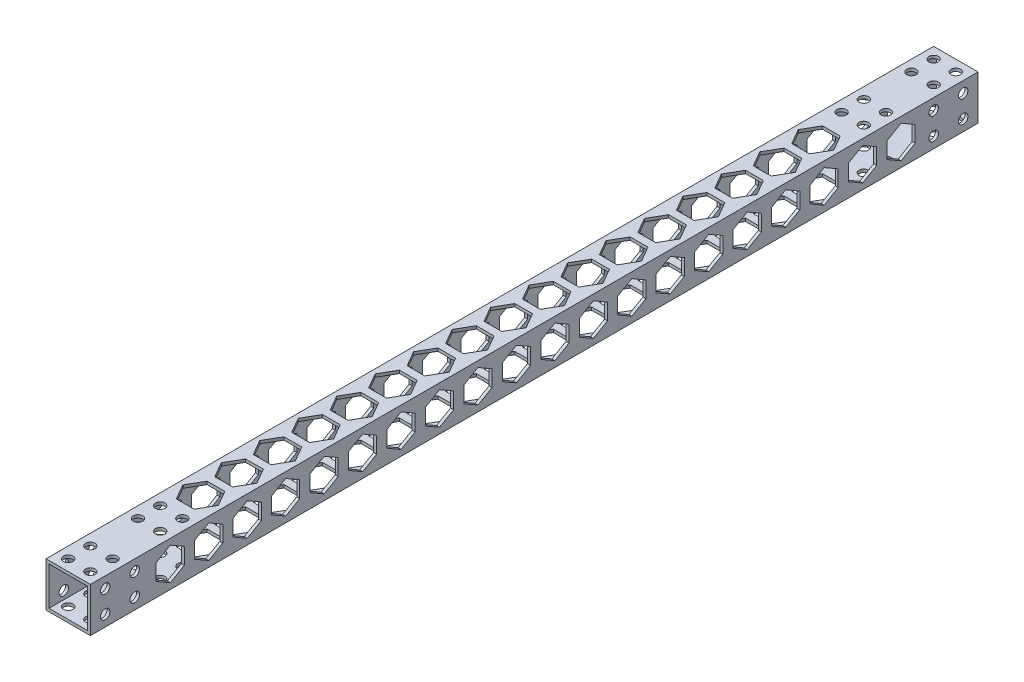
SolidWorks part; units mm, degrees
ref_plane "前视基准面" through (0, 0, 0) normal (0, 0, 1) x (1, 0, 0)
ref_plane "上视基准面" through (0, 0, 0) normal (0, 1, 0) x (1, 0, 0)
ref_plane "右视基准面" through (0, 0, 0) normal (1, 0, 0) x (0, 0, -1)
other "Configuration Table"
sketch "草图1" plane through (0, 0, 0) normal (0, 0, 1) x (1, 0, 0)
  line L1 (0, 0) -> (15, 0)
  line L2 (0, 0) -> (0, -15)
  line L3 (0, -15) -> (15, -15)
  line L4 (15, 0) -> (15, -15)
  dimension "D1" = 15
  dimension "D2" = 15
extrude "拉伸-薄壁1" add sketch "草图1" along normal blind 300 thin
sketch "草图2" plane through (15, 0, 0) normal (1, 0, 0) x (0, 0, -1)
  line L0 (-260, -2) -> (-264.7631, -4.75)
  line L1 (-300, 0) -> (0, 0) construction
  line L2 (-300, -15) -> (0, -15) construction
  line L3 (-290, 0) -> (-290, -15) construction
  line L4 (-300, -15) -> (-300, 0) construction
  line L5 (-300, -7.5) -> (-290, -7.5) construction
  line L6 (-10, 0) -> (-10, -15) construction
  line L7 (0, -7.5) -> (-10, -7.5) construction
  line L8 (0, -15) -> (0, 0) construction
  line L9 (-273, -7.5) -> (-290, -7.5) construction
  line L10 (-273, -2) -> (-277.7631, -4.75)
  line L11 (-277.7631, -4.75) -> (-277.7631, -10.25)
  line L12 (-277.7631, -10.25) -> (-273, -13)
  line L13 (-273, -13) -> (-268.2369, -10.25)
  line L14 (-268.2369, -10.25) -> (-268.2369, -4.75)
  line L15 (-268.2369, -4.75) -> (-273, -2)
  line L16 (-255.2369, -4.75) -> (-260, -2)
  line L17 (-255.2369, -10.25) -> (-255.2369, -4.75)
  line L18 (-260, -13) -> (-255.2369, -10.25)
  line L19 (-264.7631, -10.25) -> (-260, -13)
  line L20 (-264.7631, -4.75) -> (-264.7631, -10.25)
  line L21 (-247, -2) -> (-251.7631, -4.75)
  line L22 (-242.2369, -4.75) -> (-247, -2)
  line L23 (-242.2369, -10.25) -> (-242.2369, -4.75)
  line L24 (-247, -13) -> (-242.2369, -10.25)
  line L25 (-251.7631, -10.25) -> (-247, -13)
  line L26 (-251.7631, -4.75) -> (-251.7631, -10.25)
  line L27 (-234, -2) -> (-238.7631, -4.75)
  line L28 (-229.2369, -4.75) -> (-234, -2)
  line L29 (-229.2369, -10.25) -> (-229.2369, -4.75)
  line L30 (-234, -13) -> (-229.2369, -10.25)
  line L31 (-238.7631, -10.25) -> (-234, -13)
  line L32 (-238.7631, -4.75) -> (-238.7631, -10.25)
  line L33 (-221, -2) -> (-225.7631, -4.75)
  line L34 (-216.2369, -4.75) -> (-221, -2)
  line L35 (-216.2369, -10.25) -> (-216.2369, -4.75)
  line L36 (-221, -13) -> (-216.2369, -10.25)
  line L37 (-225.7631, -10.25) -> (-221, -13)
  line L38 (-225.7631, -4.75) -> (-225.7631, -10.25)
  line L39 (-208, -2) -> (-212.7631, -4.75)
  line L40 (-203.2369, -4.75) -> (-208, -2)
  line L41 (-203.2369, -10.25) -> (-203.2369, -4.75)
  line L42 (-208, -13) -> (-203.2369, -10.25)
  line L43 (-212.7631, -10.25) -> (-208, -13)
  line L44 (-212.7631, -4.75) -> (-212.7631, -10.25)
  line L45 (-195, -2) -> (-199.7631, -4.75)
  line L46 (-190.2369, -4.75) -> (-195, -2)
  line L47 (-190.2369, -10.25) -> (-190.2369, -4.75)
  line L48 (-195, -13) -> (-190.2369, -10.25)
  line L49 (-199.7631, -10.25) -> (-195, -13)
  line L50 (-199.7631, -4.75) -> (-199.7631, -10.25)
  line L51 (-182, -2) -> (-186.7631, -4.75)
  line L52 (-177.2369, -4.75) -> (-182, -2)
  line L53 (-177.2369, -10.25) -> (-177.2369, -4.75)
  line L54 (-182, -13) -> (-177.2369, -10.25)
  line L55 (-186.7631, -10.25) -> (-182, -13)
  line L56 (-186.7631, -4.75) -> (-186.7631, -10.25)
  line L57 (-169, -2) -> (-173.7631, -4.75)
  line L58 (-164.2369, -4.75) -> (-169, -2)
  line L59 (-164.2369, -10.25) -> (-164.2369, -4.75)
  line L60 (-169, -13) -> (-164.2369, -10.25)
  line L61 (-173.7631, -10.25) -> (-169, -13)
  line L62 (-173.7631, -4.75) -> (-173.7631, -10.25)
  line L63 (-156, -2) -> (-160.7631, -4.75)
  line L64 (-151.2369, -4.75) -> (-156, -2)
  line L65 (-151.2369, -10.25) -> (-151.2369, -4.75)
  line L66 (-156, -13) -> (-151.2369, -10.25)
  line L67 (-160.7631, -10.25) -> (-156, -13)
  line L68 (-160.7631, -4.75) -> (-160.7631, -10.25)
  line L69 (-143, -2) -> (-147.7631, -4.75)
  line L70 (-138.2369, -4.75) -> (-143, -2)
  line L71 (-138.2369, -10.25) -> (-138.2369, -4.75)
  line L72 (-143, -13) -> (-138.2369, -10.25)
  line L73 (-147.7631, -10.25) -> (-143, -13)
  line L74 (-147.7631, -4.75) -> (-147.7631, -10.25)
  line L75 (-130, -2) -> (-134.7631, -4.75)
  line L76 (-125.2369, -4.75) -> (-130, -2)
  line L77 (-125.2369, -10.25) -> (-125.2369, -4.75)
  line L78 (-130, -13) -> (-125.2369, -10.25)
  line L79 (-134.7631, -10.25) -> (-130, -13)
  line L80 (-134.7631, -4.75) -> (-134.7631, -10.25)
  line L81 (-117, -2) -> (-121.7631, -4.75)
  line L82 (-112.2369, -4.75) -> (-117, -2)
  line L83 (-112.2369, -10.25) -> (-112.2369, -4.75)
  line L84 (-117, -13) -> (-112.2369, -10.25)
  line L85 (-121.7631, -10.25) -> (-117, -13)
  line L86 (-121.7631, -4.75) -> (-121.7631, -10.25)
  line L87 (-104, -2) -> (-108.7631, -4.75)
  line L88 (-99.2369, -4.75) -> (-104, -2)
  line L89 (-99.2369, -10.25) -> (-99.2369, -4.75)
  line L90 (-104, -13) -> (-99.2369, -10.25)
  line L91 (-108.7631, -10.25) -> (-104, -13)
  line L92 (-108.7631, -4.75) -> (-108.7631, -10.25)
  line L93 (-91, -2) -> (-95.7631, -4.75)
  line L94 (-86.2369, -4.75) -> (-91, -2)
  line L95 (-86.2369, -10.25) -> (-86.2369, -4.75)
  line L96 (-91, -13) -> (-86.2369, -10.25)
  line L97 (-95.7631, -10.25) -> (-91, -13)
  line L98 (-95.7631, -4.75) -> (-95.7631, -10.25)
  line L99 (-78, -2) -> (-82.7631, -4.75)
  line L100 (-73.2369, -4.75) -> (-78, -2)
  line L101 (-73.2369, -10.25) -> (-73.2369, -4.75)
  line L102 (-78, -13) -> (-73.2369, -10.25)
  line L103 (-82.7631, -10.25) -> (-78, -13)
  line L104 (-82.7631, -4.75) -> (-82.7631, -10.25)
  line L105 (-65, -2) -> (-69.7631, -4.75)
  line L106 (-60.2369, -4.75) -> (-65, -2)
  line L107 (-60.2369, -10.25) -> (-60.2369, -4.75)
  line L108 (-65, -13) -> (-60.2369, -10.25)
  line L109 (-69.7631, -10.25) -> (-65, -13)
  line L110 (-69.7631, -4.75) -> (-69.7631, -10.25)
  line L111 (-52, -2) -> (-56.7631, -4.75)
  line L112 (-47.2369, -4.75) -> (-52, -2)
  line L113 (-47.2369, -10.25) -> (-47.2369, -4.75)
  line L114 (-52, -13) -> (-47.2369, -10.25)
  line L115 (-56.7631, -10.25) -> (-52, -13)
  line L116 (-56.7631, -4.75) -> (-56.7631, -10.25)
  line L117 (-39, -2) -> (-43.7631, -4.75)
  line L118 (-34.2369, -4.75) -> (-39, -2)
  line L119 (-34.2369, -10.25) -> (-34.2369, -4.75)
  line L120 (-39, -13) -> (-34.2369, -10.25)
  line L121 (-43.7631, -10.25) -> (-39, -13)
  line L122 (-43.7631, -4.75) -> (-43.7631, -10.25)
  line L123 (-26, -2) -> (-30.7631, -4.75)
  line L124 (-21.2369, -4.75) -> (-26, -2)
  line L125 (-21.2369, -10.25) -> (-21.2369, -4.75)
  line L126 (-26, -13) -> (-21.2369, -10.25)
  line L127 (-30.7631, -10.25) -> (-26, -13)
  line L128 (-30.7631, -4.75) -> (-30.7631, -10.25)
  circle A0 centre (-295, -3.75) radius 1.6
  circle A1 centre (-295, -11.25) radius 1.6
  circle A2 centre (-285, -11.25) radius 1.6
  circle A3 centre (-285, -3.75) radius 1.6
  circle A8 centre (-5, -3.75) radius 1.6
  circle A9 centre (-5, -11.25) radius 1.6
  circle A10 centre (-15, -11.25) radius 1.6
  circle A11 centre (-15, -3.75) radius 1.6
  circle A12 centre (-273, -7.5) radius 4.7631 construction
  dimension "D2" = 3.2
  dimension "D6" = 3.2
  dimension "D1" = 10
  dimension "D3" = 5
  dimension "D4" = 3.75
  dimension "D5" = 10
  dimension "D7" = 3.75
  dimension "D8" = 5
  dimension "D9" = 5.5
  dimension "D10" = 17
  dimension "D12" = 13
  dimension "D11" = 20
extrude "切除-拉伸1" cut sketch "草图2" against normal through all
sketch "草图3" plane through (0, 0, 0) normal (0, 1, 0) x (1, 0, 0)
  line L0 (7.5, 0) -> (7.5, -300) construction
  line L1 (15, 0) -> (0, 0) construction
  line L2 (15, -300) -> (0, -300) construction
  line L3 (15, -150) -> (0, -150) construction
  line L4 (15, -300) -> (15, 0) construction
  line L5 (0, -300) -> (0, 0) construction
  line L6 (0, -7.5) -> (15, -7.5) construction
  line L7 (0, -292.5) -> (15, -292.5) construction
  line L8 (10.5, -55.0538) -> (4.5, -55.0538)
  line L9 (4.5, -42.0538) -> (1.5, -47.25)
  line L10 (1.5, -47.25) -> (4.5, -52.4462)
  line L11 (4.5, -52.4462) -> (10.5, -52.4462)
  line L12 (10.5, -52.4462) -> (13.5, -47.25)
  line L13 (13.5, -47.25) -> (10.5, -42.0538)
  line L14 (10.5, -42.0538) -> (4.5, -42.0538)
  line L15 (13.5, -60.25) -> (10.5, -55.0538)
  line L16 (10.5, -65.4462) -> (13.5, -60.25)
  line L17 (4.5, -65.4462) -> (10.5, -65.4462)
  line L18 (1.5, -60.25) -> (4.5, -65.4462)
  line L19 (4.5, -55.0538) -> (1.5, -60.25)
  line L20 (10.5, -68.0538) -> (4.5, -68.0538)
  line L21 (13.5, -73.25) -> (10.5, -68.0538)
  line L22 (10.5, -78.4462) -> (13.5, -73.25)
  line L23 (4.5, -78.4462) -> (10.5, -78.4462)
  line L24 (1.5, -73.25) -> (4.5, -78.4462)
  line L25 (4.5, -68.0538) -> (1.5, -73.25)
  line L26 (10.5, -81.0538) -> (4.5, -81.0538)
  line L27 (13.5, -86.25) -> (10.5, -81.0538)
  line L28 (10.5, -91.4462) -> (13.5, -86.25)
  line L29 (4.5, -91.4462) -> (10.5, -91.4462)
  line L30 (1.5, -86.25) -> (4.5, -91.4462)
  line L31 (4.5, -81.0538) -> (1.5, -86.25)
  line L32 (10.5, -94.0538) -> (4.5, -94.0538)
  line L33 (13.5, -99.25) -> (10.5, -94.0538)
  line L34 (10.5, -104.4462) -> (13.5, -99.25)
  line L35 (4.5, -104.4462) -> (10.5, -104.4462)
  line L36 (1.5, -99.25) -> (4.5, -104.4462)
  line L37 (4.5, -94.0538) -> (1.5, -99.25)
  line L38 (10.5, -107.0538) -> (4.5, -107.0538)
  line L39 (13.5, -112.25) -> (10.5, -107.0538)
  line L40 (10.5, -117.4462) -> (13.5, -112.25)
  line L41 (4.5, -117.4462) -> (10.5, -117.4462)
  line L42 (1.5, -112.25) -> (4.5, -117.4462)
  line L43 (4.5, -107.0538) -> (1.5, -112.25)
  line L44 (10.5, -120.0538) -> (4.5, -120.0538)
  line L45 (13.5, -125.25) -> (10.5, -120.0538)
  line L46 (10.5, -130.4462) -> (13.5, -125.25)
  line L47 (4.5, -130.4462) -> (10.5, -130.4462)
  line L48 (1.5, -125.25) -> (4.5, -130.4462)
  line L49 (4.5, -120.0538) -> (1.5, -125.25)
  line L50 (10.5, -133.0538) -> (4.5, -133.0538)
  line L51 (13.5, -138.25) -> (10.5, -133.0538)
  line L52 (10.5, -143.4462) -> (13.5, -138.25)
  line L53 (4.5, -143.4462) -> (10.5, -143.4462)
  line L54 (1.5, -138.25) -> (4.5, -143.4462)
  line L55 (4.5, -133.0538) -> (1.5, -138.25)
  line L56 (10.5, -146.0538) -> (4.5, -146.0538)
  line L57 (13.5, -151.25) -> (10.5, -146.0538)
  line L58 (10.5, -156.4462) -> (13.5, -151.25)
  line L59 (4.5, -156.4462) -> (10.5, -156.4462)
  line L60 (1.5, -151.25) -> (4.5, -156.4462)
  line L61 (4.5, -146.0538) -> (1.5, -151.25)
  line L62 (10.5, -159.0538) -> (4.5, -159.0538)
  line L63 (13.5, -164.25) -> (10.5, -159.0538)
  line L64 (10.5, -169.4462) -> (13.5, -164.25)
  line L65 (4.5, -169.4462) -> (10.5, -169.4462)
  line L66 (1.5, -164.25) -> (4.5, -169.4462)
  line L67 (4.5, -159.0538) -> (1.5, -164.25)
  line L68 (10.5, -172.0538) -> (4.5, -172.0538)
  line L69 (13.5, -177.25) -> (10.5, -172.0538)
  line L70 (10.5, -182.4462) -> (13.5, -177.25)
  line L71 (4.5, -182.4462) -> (10.5, -182.4462)
  line L72 (1.5, -177.25) -> (4.5, -182.4462)
  line L73 (4.5, -172.0538) -> (1.5, -177.25)
  line L74 (10.5, -185.0538) -> (4.5, -185.0538)
  line L75 (13.5, -190.25) -> (10.5, -185.0538)
  line L76 (10.5, -195.4462) -> (13.5, -190.25)
  line L77 (4.5, -195.4462) -> (10.5, -195.4462)
  line L78 (1.5, -190.25) -> (4.5, -195.4462)
  line L79 (4.5, -185.0538) -> (1.5, -190.25)
  line L80 (10.5, -198.0538) -> (4.5, -198.0538)
  line L81 (13.5, -203.25) -> (10.5, -198.0538)
  line L82 (10.5, -208.4462) -> (13.5, -203.25)
  line L83 (4.5, -208.4462) -> (10.5, -208.4462)
  line L84 (1.5, -203.25) -> (4.5, -208.4462)
  line L85 (4.5, -198.0538) -> (1.5, -203.25)
  line L86 (10.5, -211.0538) -> (4.5, -211.0538)
  line L87 (13.5, -216.25) -> (10.5, -211.0538)
  line L88 (10.5, -221.4462) -> (13.5, -216.25)
  line L89 (4.5, -221.4462) -> (10.5, -221.4462)
  line L90 (1.5, -216.25) -> (4.5, -221.4462)
  line L91 (4.5, -211.0538) -> (1.5, -216.25)
  line L134 (0, -31.1) -> (15, -31.1) construction
  line L135 (10.5, -224.0538) -> (4.5, -224.0538)
  line L136 (13.5, -229.25) -> (10.5, -224.0538)
  line L137 (10.5, -234.4462) -> (13.5, -229.25)
  line L138 (4.5, -234.4462) -> (10.5, -234.4462)
  line L139 (1.5, -229.25) -> (4.5, -234.4462)
  line L140 (4.5, -224.0538) -> (1.5, -229.25)
  line L159 (0, -268.9) -> (15, -268.9) construction
  line L160 (10.5, -237.0538) -> (4.5, -237.0538)
  line L161 (13.5, -242.25) -> (10.5, -237.0538)
  line L162 (10.5, -247.4462) -> (13.5, -242.25)
  line L163 (4.5, -247.4462) -> (10.5, -247.4462)
  line L164 (1.5, -242.25) -> (4.5, -247.4462)
  line L165 (4.5, -237.0538) -> (1.5, -242.25)
  line L166 (10.5, -250.0538) -> (4.5, -250.0538)
  line L167 (13.5, -255.25) -> (10.5, -250.0538)
  line L168 (10.5, -260.4462) -> (13.5, -255.25)
  line L169 (4.5, -260.4462) -> (10.5, -260.4462)
  line L170 (1.5, -255.25) -> (4.5, -260.4462)
  line L171 (4.5, -250.0538) -> (1.5, -255.25)
  circle A0 centre (3.75, -3.75) radius 1.6
  circle A1 centre (11.25, -3.75) radius 1.6
  circle A2 centre (11.25, -11.25) radius 1.6
  circle A3 centre (3.75, -11.25) radius 1.6
  circle A28 centre (3.75, -288.75) radius 1.6
  circle A29 centre (11.25, -288.75) radius 1.6
  circle A30 centre (11.25, -296.25) radius 1.6
  circle A31 centre (3.75, -296.25) radius 1.6
  circle A32 centre (7.5, -47.25) radius 5.1962 construction
  circle A33 centre (3.75, -27.35) radius 1.6
  circle A34 centre (11.25, -27.35) radius 1.6
  circle A35 centre (11.25, -34.85) radius 1.6
  circle A36 centre (3.75, -34.85) radius 1.6
  circle A37 centre (3.75, -265.15) radius 1.6
  circle A38 centre (11.25, -265.15) radius 1.6
  circle A39 centre (11.25, -272.65) radius 1.6
  circle A40 centre (3.75, -272.65) radius 1.6
  dimension "D1" = 3.2
  dimension "D7" = 31.1
  dimension "D8" = 3.2
  dimension "D2" = 3.75
  dimension "D3" = 7.5
  dimension "D4" = 3.75
  dimension "D6" = 36
  dimension "D9" = 3.75
  dimension "D5" = 6
  dimension "D11" = 13
  dimension "D12" = 3.75
  dimension "D10" = 17
extrude "切除-拉伸2" cut sketch "草图3" against normal through all
